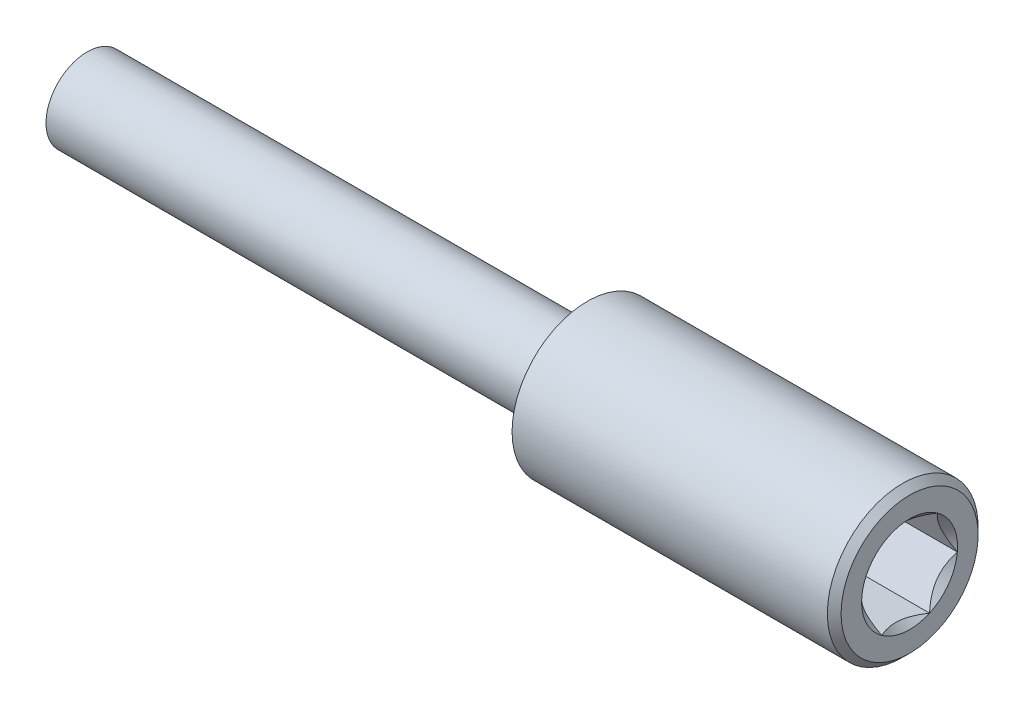
SolidWorks part; units mm, degrees
other "Marca1"
sketch "Croquis8" plane through (60, 5.5, 5.5) normal (0.9629, 0.0363, 0.2675) x (-0.2636, -0.0868, 0.9607)
ref_plane "Alzado" through (0, 0, 0) normal (0, 0, 1) x (1, 0, 0)
ref_plane "Planta" through (0, 0, 0) normal (0, 1, 0) x (1, 0, 0)
ref_plane "Vista lateral" through (0, 0, 0) normal (1, 0, 0) x (0, 0, -1)
sketch "Croquis1" plane through (0, 0, 0) normal (0, 1, 0) x (1, 0, 0)
  line L0 (0, 0) -> (49.5566, 0)
  line L1 (60, 3.5) -> (60, 5)
  line L2 (59.5, 5.5) -> (36.5, 5.5)
  line L3 (36.5, 5.5) -> (36.5, 3)
  line L4 (36.5, 3) -> (0, 3)
  line L5 (0, 3) -> (0, 0)
  line L6 (60, 5) -> (59.5, 5.5)
  line L7 (59.5, 3) -> (58, 3)
  line L9 (58, 3) -> (58, 2.5)
  line L10 (58, 2.5) -> (51, 2.5)
  line L11 (51, 2.5) -> (49.5566, 0)
  line L12 (59.5, 3) -> (60, 3.5)
  point P3 (60, 5.5)
  point P9 (60, 3)
  dimension "D1" = 5.5
  dimension "D2" = 3
  dimension "D3" = 3
  dimension "D4" = 23.5
  dimension "D5" = 0.5
  dimension "D6" = 45
  dimension "D7" = 3
  dimension "D8" = 2
  dimension "D9" = 60
  dimension "D10" = 0.5
  dimension "D11" = 7
revolve "Revolución1" add sketch "Croquis1" angle 360 about L0
sketch "Croquis3" plane through (60, 0, 0) normal (1, 0, 0) x (0, 0, -1)
  line L13 (3.4842, -0.3325) -> (2.03, 2.8511)
  line L14 (2.03, 2.8511) -> (-1.4541, 3.1836)
  line L15 (-1.4541, 3.1836) -> (-3.4842, 0.3325)
  line L16 (-3.4842, 0.3325) -> (-2.03, -2.8511)
  line L17 (-2.03, -2.8511) -> (1.4541, -3.1836)
  line L18 (1.4541, -3.1836) -> (3.4842, -0.3325)
  circle A0 centre (0, 0) radius 3.5 construction
extrude "Cortar-Extruir2" cut sketch "Croquis3" against normal blind 5
